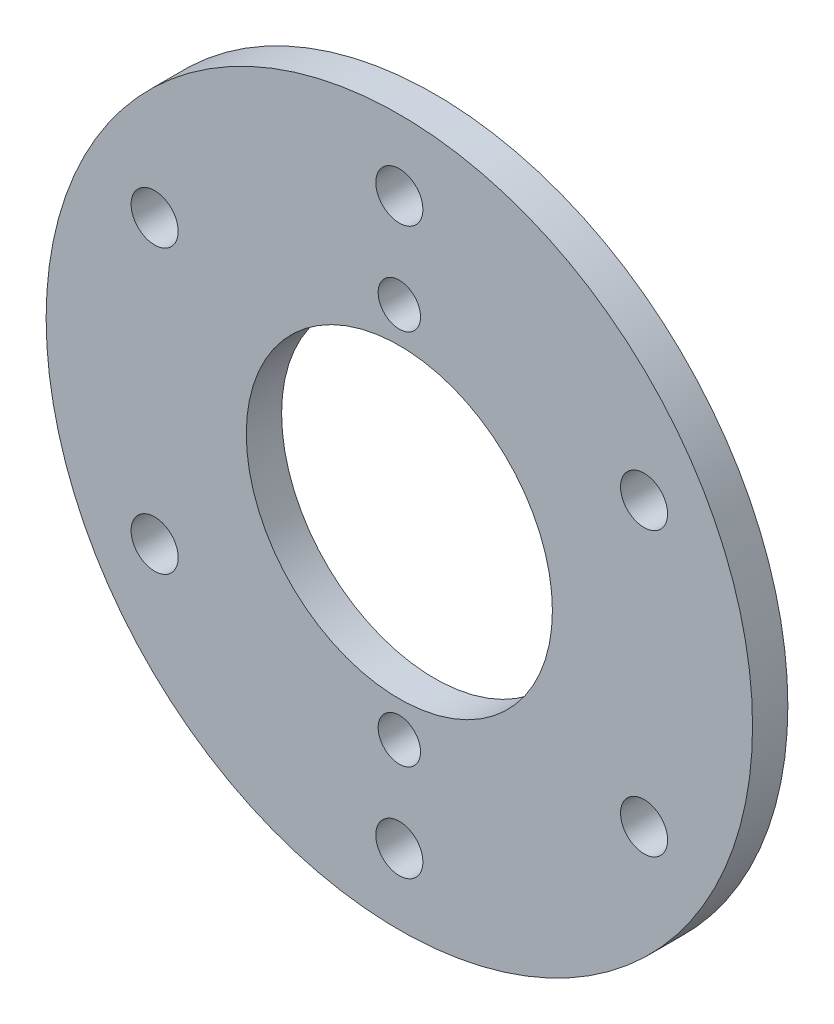
SolidWorks part; units mm, degrees
ref_plane "Front Plane" through (0, 0, 0) normal (0, 0, 1) x (1, 0, 0)
ref_plane "Top Plane" through (0, 0, 0) normal (0, 1, 0) x (1, 0, 0)
ref_plane "Right Plane" through (0, 0, 0) normal (1, 0, 0) x (0, 0, -1)
sketch "Sketch1" plane through (0, 0, 0) normal (0, 0, 1) x (1, 0, 0)
  circle A0 centre (0, 0) radius 150
  circle A1 centre (0, 0) radius 65
  circle A2 centre (0, 0) radius 120 construction
  dimension "D1" = 300
  dimension "D2" = 130
  dimension "D3" = 240
extrude "Boss-Extrude1" add sketch "Sketch1" along normal blind 15
sketch "Sketch2" plane through (0, 0, 15) normal (0, 0, 1) x (1, 0, 0)
  line L0 (0, 150) -> (0, -150) construction
  line L1 (-150, 0) -> (150, 0) construction
  circle A0 centre (0, 0) radius 150 construction
  circle A1 centre (0, 0) radius 120 construction
  dimension "D1" = 240
hole_wizard "Ø1.0mm Dowel Hole1" positions "Sketch6" profile "Sketch8" hole size "Ø1.0" standard "ISO" end condition through all
sketch "Sketch6" plane through (0, 0, 15) normal (0, 0, 1) x (1, 0, 0)
  line L0 (0, 150) -> (0, -150) construction
  circle A0 centre (0, 0) radius 120 construction
  point P0 (0, 120)
sketch "Sketch8" plane through (0, 120, 15) normal (1, 0, 0) x (0, -1, 0)
  line L0 (0, 0) -> (0, 15)
  line L1 (0, 15) -> (10, 15)
  line L2 (10, 15) -> (10, 0)
  line L5 (10, 0) -> (0, 0)
  line L11 (0, -6.35) -> (0, 107.95) construction
  dimension "Thru Hole Dia." = 20
  dimension "Thru Hole Depth" = 15
pattern_circular "CirPattern1" count 6 over 360 about axis through (0, 0, 0) along (0, 0, 1) of "Ø1.0mm Dowel Hole1"
hole_wizard "Ø1.0mm Dowel Hole2" positions "Sketch9" profile "Sketch10" hole size "Ø1.0" standard "ISO" end condition through all
sketch "Sketch9" plane through (0, 0, 15) normal (0, 0, 1) x (1, 0, 0)
  line L0 (0, 150) -> (0, -150) construction
  point P0 (0, 80)
  point P4 (0, -80)
  dimension "D1" = 160
  dimension "D2" = 80
sketch "Sketch10" plane through (0, 80, 15) normal (1, 0, 0) x (0, -1, 0)
  line L0 (0, 0) -> (0, 15)
  line L1 (0, 15) -> (9, 15)
  line L2 (9, 15) -> (9, 0)
  line L5 (9, 0) -> (0, 0)
  line L11 (0, -6.35) -> (0, 107.95) construction
  dimension "Thru Hole Dia." = 18
  dimension "Thru Hole Depth" = 15
